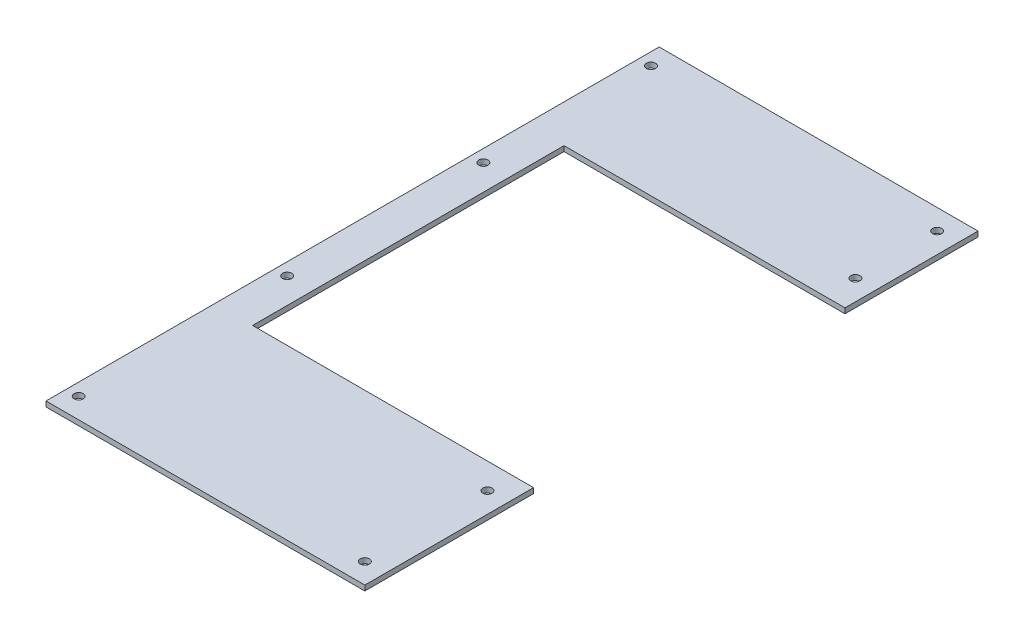
SolidWorks part; units mm, degrees
ref_plane "Front Plane" through (0, 0, 0) normal (1, 0, 0) x (0, 1, 0)
ref_plane "Top Plane" through (0, 0, 0) normal (0, 0, 1) x (0, 1, 0)
ref_plane "Right Plane" through (0, 0, 0) normal (0, 1, 0) x (-1, 0, 0)
sketch "Sketch1" plane through (0, 0, 0) normal (0, 1, 0) x (-1, 0, 0)
  line L0 (187.5, 235) -> (187.5, 275) construction
  line L1 (0, 275) -> (200, 275)
  line L2 (0, 275) -> (0, 375)
  line L3 (0, 375) -> (200, 375)
  line L4 (200, 275) -> (200, 375)
  line L5 (0, 275) -> (200, 375) construction
  line L6 (0, 375) -> (200, 275) construction
  line L7 (200, 275) -> (175, 275)
  line L8 (200, 275) -> (200, 0)
  line L9 (200, 0) -> (175, 0)
  line L10 (175, 275) -> (175, 0)
  line L11 (200, 275) -> (175, 0) construction
  line L12 (200, 0) -> (175, 275) construction
  line L13 (175, 0) -> (0, 0)
  line L14 (175, 0) -> (175, 75)
  line L15 (175, 75) -> (0, 75)
  line L16 (0, 0) -> (0, 75)
  line L17 (175, 0) -> (0, 75) construction
  line L18 (175, 75) -> (0, 0) construction
  line L19 (187.5, 115) -> (187.5, 0) construction
  circle A0 centre (12.5, 362.5) radius 2.8
  circle A1 centre (12.5, 287.5) radius 2.8
  circle A2 centre (187.5, 362.5) radius 2.8
  circle A3 centre (12.5, 62.5) radius 2.8
  circle A4 centre (12.5, 12.5) radius 2.8
  circle A5 centre (187.5, 12.5) radius 2.8
  circle A7 centre (187.5, 235) radius 2.8
  circle A8 centre (187.5, 115) radius 2.8
  point P4 (100, 325)
  point P8 (187.5, 137.5)
  point P12 (87.5, 37.5)
  point P14 (0, 37.5)
  point P33 (187.5, 362.5)
  dimension "D7" = 5.6
  dimension "D1" = 25
  dimension "D2" = 100
  dimension "D3" = 200
  dimension "D4" = 200
  dimension "D5" = 200
  dimension "D6" = 75
  dimension "D8" = 12.5
  dimension "D9" = 12.5
  dimension "D10" = 12.5
  dimension "D11" = 12.5
  dimension "D12" = 12.5
  dimension "D13" = 12.5
  dimension "D14" = 12.5
  dimension "D15" = 12.5
  dimension "D16" = 12.5
  dimension "D17" = 12.5
  dimension "D18" = 12.5
  dimension "D19" = 12.5
  dimension "D20" = 40
  dimension "D21" = 40
extrude "Boss-Extrude1" add sketch "Sketch1" along normal blind 3.175 contours L1 L4 L3 L2 A2 A1 A0 | L1 L10 L9 L8 A8 A7 A5 | L16 L13 L10 L15 A4 A3
sketch "Sketch2" plane through (0, 3.175, 0) normal (0, 1, 0) x (-1, 0, 0)
  line L0 (175, 275) -> (175, 75) construction
  line L1 (0, 275) -> (175, 275)
  line L2 (0, 275) -> (0, 271.825)
  line L3 (0, 271.825) -> (175, 271.825)
  line L4 (175, 275) -> (175, 271.825)
  line L5 (0, 275) -> (175, 271.825) construction
  line L6 (0, 271.825) -> (175, 275) construction
  line L7 (175, 75) -> (0, 75) construction
  line L8 (175, 271.825) -> (171.825, 271.825)
  line L9 (175, 271.825) -> (175, 75)
  line L10 (175, 75) -> (171.825, 75)
  line L11 (171.825, 271.825) -> (171.825, 75)
  line L12 (175, 271.825) -> (171.825, 75) construction
  line L13 (175, 75) -> (171.825, 271.825) construction
  line L15 (0, 75) -> (171.825, 75)
  line L16 (0, 75) -> (0, 81.35)
  line L17 (0, 81.35) -> (171.825, 81.35)
  line L18 (171.825, 75) -> (171.825, 81.35)
  line L19 (0, 75) -> (171.825, 81.35) construction
  line L20 (0, 81.35) -> (171.825, 75) construction
  point P4 (87.5, 273.4125)
  point P11 (173.4125, 173.4125)
  point P17 (85.9125, 78.175)
  line M9 (0, 275) -> (175, 275)
  line M10 (175, 275) -> (175, 75)
  line M11 (175, 75) -> (0, 75)
  dimension "D1" = 3.175
  dimension "D2" = 3.175
  dimension "D3" = 6.35
extrude "Boss-Extrude2" add sketch "Sketch2" against normal through all contours L2 L3 M10 M9 | L3 L11 M11 M10 | L17 L16 L11 M11
sketch "Sketch3" plane through (0, 3.175, 0) normal (0, 1, 0) x (-1, 0, 0)
  line L0 (200, 0) -> (0, 0) construction
  line L1 (200, 375) -> (195, 375)
  line L2 (200, 375) -> (200, 0)
  line L3 (200, 0) -> (195, 0)
  line L4 (195, 375) -> (195, 0)
  line L5 (200, 375) -> (195, 0) construction
  line L6 (200, 0) -> (195, 375) construction
  point P4 (197.5, 187.5)
  dimension "D1" = 5
extrude "Cut-Extrude1" cut sketch "Sketch3" against normal through all
